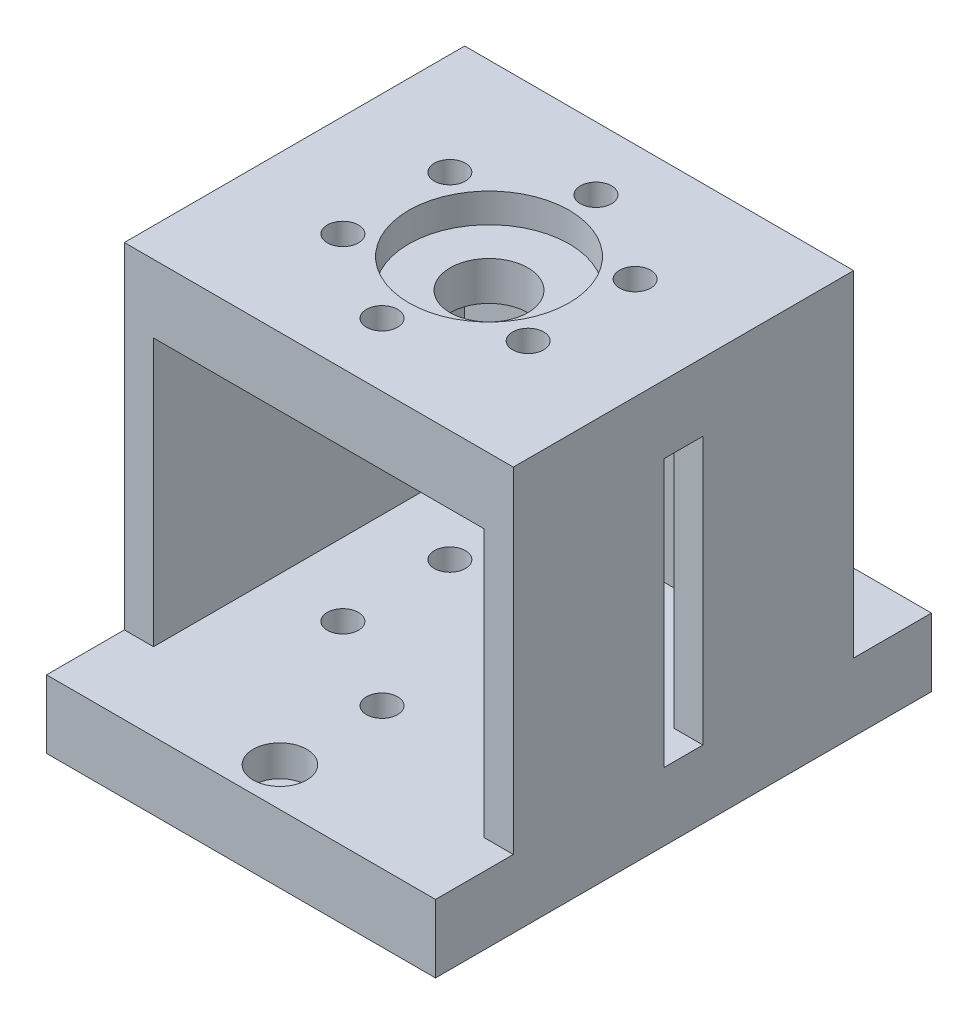
SolidWorks part; units mm, degrees
ref_plane "Front Plane" through (0, 0, 0) normal (0, 0, 1) x (1, 0, 0)
ref_plane "Top Plane" through (0, 0, 0) normal (0, 1, 0) x (1, 0, 0)
ref_plane "Right Plane" through (0, 0, 0) normal (1, 0, 0) x (0, 0, -1)
sketch "Sketch1" plane through (0, 0, 0) normal (0, 1, 0) x (1, 0, 0)
  line L1 (-20, -17.5) -> (20, -17.5)
  line L2 (-20, -17.5) -> (-20, 17.5)
  line L3 (-20, 17.5) -> (20, 17.5)
  line L4 (20, -17.5) -> (20, 17.5)
  line L5 (-20, -17.5) -> (20, 17.5) construction
  line L6 (-20, 17.5) -> (20, -17.5) construction
  point P0 (0, 0)
  dimension "D1" = 40
  dimension "D2" = 35
extrude "Boss-Extrude1" add sketch "Sketch1" along normal blind 7
sketch "Sketch2" plane through (0, 7, 0) normal (0, 1, 0) x (1, 0, 0)
  line L0 (-20, -17.5) -> (-17, -17.5)
  line L1 (-20, -17.5) -> (20, -17.5) construction
  line L2 (-17, -17.5) -> (-17, 14.5)
  line L3 (-17, 14.5) -> (17, 14.5)
  line L5 (20, -17.5) -> (20, 17.5)
  line L6 (20, 17.5) -> (-20, 17.5)
  line L7 (-20, 17.5) -> (-20, -17.5)
  line L8 (-20, -17.5) -> (20, -17.5)
  line L9 (20, -17.5) -> (20, 17.5)
  line L10 (20, 17.5) -> (-20, 17.5)
  line L11 (-20, 17.5) -> (-20, -17.5)
  line L13 (17, 14.5) -> (17, -17.5)
  line L14 (17, -17.5) -> (20, -17.5)
  dimension "D2" = 3
  dimension "D3" = 3
  dimension "D4" = 3
  dimension "D1" = 0
extrude "Boss-Extrude2" add sketch "Sketch2" along normal blind 27.5
sketch "Sketch3" plane through (0, 34.5, 0) normal (0, 1, 0) x (1, 0, 0)
  line L4 (20, -17.5) -> (20, 17.5)
  line L5 (-20, -17.5) -> (20, -17.5)
  line L6 (-20, 17.5) -> (-20, -17.5)
  line L7 (20, 17.5) -> (-20, 17.5)
  line L8 (20, -17.5) -> (20, 17.5)
  line L9 (-20, -17.5) -> (20, -17.5)
  line L10 (-20, 17.5) -> (-20, -17.5)
  line L11 (20, 17.5) -> (-20, 17.5)
  dimension "D1" = 0
extrude "Boss-Extrude3" add sketch "Sketch3" along normal blind 7
sketch "Sketch4" plane through (0, 41.5, 0) normal (0, 1, 0) x (1, 0, 0)
  line L0 (0, 28.5133) -> (0, -46.3014) construction
  line L1 (0, 0) -> (0, 11) construction
  line L2 (0, 0) -> (9.5263, 5.5) construction
  circle A0 centre (0, 0) radius 11 construction
  circle A1 centre (0, 11) radius 1.6
  circle A2 centre (9.5263, 5.5) radius 1.6
  circle A3 centre (9.5263, -5.5) radius 1.6
  circle A4 centre (0, -11) radius 1.6
  circle A5 centre (-9.5263, -5.5) radius 1.6
  circle A6 centre (-9.5263, 5.5) radius 1.6
  circle A7 centre (0, 0) radius 4
  dimension "D1" = 22
  dimension "D2" = 3.2
  dimension "D5" = 8
  dimension "D4" = 60
  dimension "D3" = 6
extrude "Cut-Extrude1" cut sketch "Sketch4" against normal blind 57
sketch "Sketch5" plane through (0, 34.5, 0) normal (0, -1, 0) x (1, 0, 0)
  circle A0 centre (0, 11) radius 2.75
  circle A1 centre (0, -11) radius 2.75
  circle A2 centre (9.5263, -5.5) radius 2.75
  circle A3 centre (9.5263, 5.5) radius 2.75
  circle A4 centre (-9.5263, 5.5) radius 2.75
  circle A5 centre (-9.5263, -5.5) radius 2.75
  dimension "D1" = 5.5
extrude "Cut-Extrude2" cut sketch "Sketch5" against normal blind 3.2
sketch "Sketch6" plane through (0, 41.5, 0) normal (0, 1, 0) x (1, 0, 0)
  circle A0 centre (0, 0) radius 8.25
  dimension "D1" = 16.5
extrude "Cut-Extrude3" cut sketch "Sketch6" against normal blind 3
sketch "Sketch7" plane through (20, 0, 0) normal (1, 0, 0) x (0, 0, -1)
  line L0 (0, 41.5) -> (0, 0) construction
  line L1 (-17.5, 41.5) -> (17.5, 41.5) construction
  line L3 (-2, 7) -> (2, 7)
  line L4 (-2, 7) -> (-2, 34.5)
  line L5 (-2, 34.5) -> (2, 34.5)
  line L6 (2, 7) -> (2, 34.5)
  line L7 (-2, 7) -> (2, 34.5) construction
  line L8 (-2, 34.5) -> (2, 7) construction
  point P5 (0, 20.75)
  point P10 (0, 12.991)
  point P13 (0, 0)
  dimension "D1" = 4
extrude "Cut-Extrude4" cut sketch "Sketch7" against normal blind 12.4
sketch "Sketch8" plane through (0, 0, 0) normal (0, 1, 0) x (1, 0, 0)
  line L0 (0, -33.9855) -> (0, 35.9323) construction
  line L4 (-20.942, 0) -> (21.8876, 0) construction
  line L15 (-20, -17.5) -> (-20, -25.5)
  line L16 (-20, -25.5) -> (20, -25.5)
  line L17 (20, -25.5) -> (20, -17.5)
  line L18 (-20, -17.5) -> (20, -17.5)
  line L19 (-20, 17.5) -> (-20, 25.5)
  line L20 (-20, 25.5) -> (20, 25.5)
  line L21 (20, 25.5) -> (20, 17.5)
  line L22 (-20, 17.5) -> (20, 17.5)
  circle A2 centre (0, -21.5) radius 1.65
  circle A3 centre (0, 21.5) radius 1.65
  point P11 (0, 0)
  point P12 (-20, -21.5)
  dimension "D2" = 3.3
  dimension "D1" = 8
extrude "Boss-Extrude4" add sketch "Sketch8" along normal up to surface (7 mm away) up to face at (9.25, 7, 0.75)
sketch "Sketch10" plane through (0, 7, 0) normal (0, 1, 0) x (1, 0, 0)
  circle A0 centre (0, 21.5) radius 2.75
  circle A1 centre (0, -21.5) radius 2.75
  dimension "D1" = 5.5
extrude "Cut-Extrude5" cut sketch "Sketch10" against normal blind 3.2
sketch "Sketch11" plane through (0, 0, 0) normal (0, -1, 0) x (1, 0, 0)
  circle A0 centre (0, 0) radius 4
  circle A1 centre (0, 0) radius 4 construction
extrude "Boss-Extrude5" add sketch "Sketch11" against normal up to surface (7 mm away) up to face at (0, 7, 24.25)
